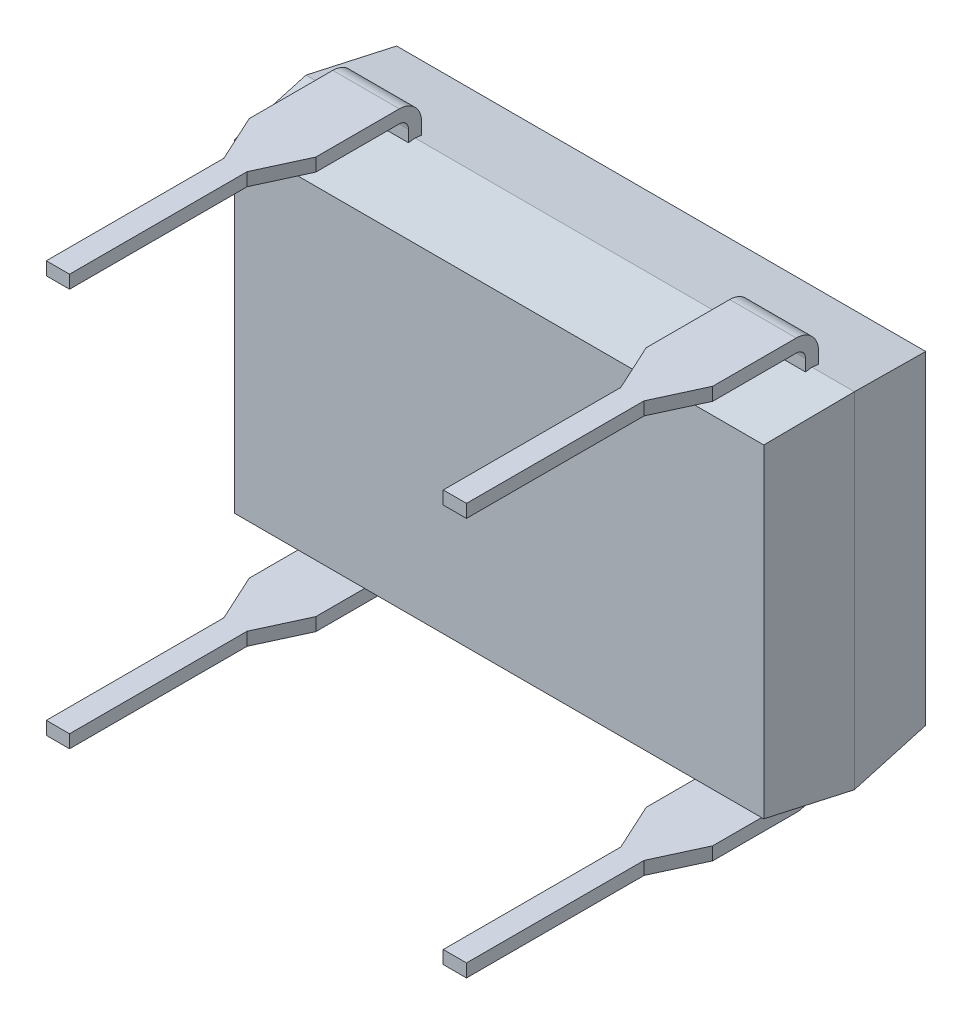
SolidWorks part; units mm, degrees
ref_plane "Plano frontal" through (0, 0, 0) normal (0, 0, 1) x (1, 0, 0)
ref_plane "Plano superior" through (0, 0, 0) normal (0, 1, 0) x (1, 0, 0)
ref_plane "Plano direito" through (0, 0, 0) normal (1, 0, 0) x (0, 0, -1)
sketch "Esboço1" plane through (0, 0, 0) normal (1, 0, 0) x (0, 0, -1)
  line L0 (0.9, 3.1) -> (0.9, -3.1)
  line L1 (0.9, -3.1) -> (2.45, -3.3)
  line L2 (2.45, -3.3) -> (4, -3.1)
  line L3 (4, -3.1) -> (4, 3.1)
  line L4 (4, 3.1) -> (2.45, 3.3)
  line L5 (2.45, 3.3) -> (0.9, 3.1)
  line L6 (2.45, 3.3) -> (2.45, -3.3) construction
  line L7 (4, 0) -> (2.45, 0) construction
  line L8 (2.45, 0) -> (0.9, 0) construction
  line L9 (0.9, 0) -> (0, 0) construction
  dimension "D1" = 6.6
  dimension "D2" = 6.2
  dimension "D3" = 3.1
  dimension "D4" = 0.9
extrude "Ressalto-extrusão1" add sketch "Esboço1" along normal mid plane 10.5
sketch "Esboço3" plane through (0, 0, 0) normal (0, 1, 0) x (1, 0, 0)
  line L0 (-5.25, 2.45) -> (-5.0199, 4.3768)
  line L1 (-5.0199, 4.3768) -> (-6.1863, 4.3768)
  line L2 (-6.1863, 4.3768) -> (-6.1863, 0.5232)
  line L3 (-6.1863, 0.5232) -> (-5.0199, 0.5232)
  line L4 (-5.0199, 0.5232) -> (-5.25, 2.45)
  line L5 (-6.1863, 2.45) -> (-5.25, 2.45) construction
  line L6 (-5.25, 0.9) -> (-5.25, 2.45) construction
  dimension "D1" = 6.81
  dimension "D2" = 3.8537
  dimension "D3" = 1.1665
extrude "Corte-extrusão2" cut sketch "Esboço3" against normal mid plane 7.1
mirror "Espelhar1" about plane through (0, 0, 0) normal (1, 0, 0) of "Corte-extrusão2"
sketch "Esboço8" plane through (0, 0, -4) normal (0, 0, -1) x (-1, 0, 0)
  line L0 (5.0649, -3.1) -> (5.0649, 3.1) construction
  circle A0 centre (5.0649, 0) radius 1
  dimension "D1" = 2
extrude "Corte-extrusão5" cut sketch "Esboço8" against normal up to vertex (1.55 mm away)
ref_plane "Plano1" through (0, 3.3, 0) normal (0, 1, 0) x (1, 0, 0)
sketch "Esboço6" plane through (0, 3.3, 0) normal (0, 1, 0) x (1, 0, 0)
  line L0 (-3.1625, 2.45) -> (0, 2.45) construction
  line L1 (-4.4375, 2.575) -> (-3.1625, 2.575)
  line L2 (-4.4375, 2.575) -> (-4.4375, 2.325)
  line L3 (-4.4375, 2.325) -> (-3.1625, 2.325)
  line L4 (-3.1625, 2.575) -> (-3.1625, 2.325)
  line L5 (5.25, 2.45) -> (-5.25, 2.45) construction
  line L6 (-3.8, 2.575) -> (-3.8, 2.325) construction
  line L7 (0, 5.2905) -> (0, -0.8303) construction
  point P14 (0, 0)
  dimension "D1" = 0.25
  dimension "D2" = 1.275
  dimension "D3" = 1.45
extrude "Ressalto-extrusão2" add sketch "Esboço6" along normal mid plane 0.05
sketch "Esboço7" plane through (0, 3.325, 0) normal (0, 1, 0) x (1, 0, 0)
  line L0 (-4.4375, 2.575) -> (-4.4375, 2.325) construction
  line L1 (-3.1625, 2.575) -> (-4.4375, 2.575) construction
  line L2 (-3.1625, 2.325) -> (-3.1625, 2.575) construction
  line L3 (-4.4375, 2.325) -> (-3.1625, 2.325) construction
  line L4 (-4.4375, 2.575) -> (-4.4375, 2.325)
  line L5 (-3.1625, 2.575) -> (-4.4375, 2.575)
  line L6 (-3.1625, 2.325) -> (-3.1625, 2.575)
  line L7 (-4.4375, 2.325) -> (-3.1625, 2.325)
  line L8 (-4.4375, 2.45) -> (-3.1625, 2.45) construction
sketch3d "3DSketch1"
  line L0 (-3.8, 3.325, -2.45) -> (-3.8, 3.51, -2.45)
  line L1 (-3.8, 3.325, -2.45) -> (-3.8, 0, -2.45) construction
  line L2 (-4.4375, 3.325, -2.45) -> (-3.1625, 3.325, -2.45) construction
  line L3 (-3.8, 3.81, -2.15) -> (-3.8, 3.81, 0.35)
  line L4 (-3.8, 0, -2.45) -> (0, 0, 0) construction
  line L5 (-5.0649, 2.7669, -0.9) -> (-4.7149, 5.6108, -0.9539) construction
  line L6 (-5.0649, 3.1, -0.9) -> (-5.0649, -3.1, -0.9) construction
  arc A0 (-3.8, 3.51, -2.45) -> (-3.8, 3.81, -2.15) centre (-3.8, 3.51, -2.15) ccw
  point P5 (-3.5, 3.51, -2.15)
  dimension "D3" = 0.3
  dimension "D1" = 2.8
  dimension "D2" = 3.81
sweep "Varredura1" add profiles "Esboço7" path "3DSketch1"
sketch "Esboço9" plane through (0, 3.935, 0) normal (0, 1, 0) x (1, 0, 0)
  line L0 (-4.0225, -0.35) -> (-4.4375, 0.55)
  line L1 (-3.1625, -0.35) -> (-4.4375, -0.35) construction
  line L3 (-4.4375, 2.15) -> (-4.4375, -0.35) construction
  line L4 (-4.4375, 0.55) -> (-4.4375, -0.55)
  line L5 (-4.4375, -0.55) -> (-3.1625, -0.55)
  line L6 (-3.1625, -0.55) -> (-3.1625, 0.55)
  line L7 (-3.1625, 2.15) -> (-3.1625, -0.35) construction
  line L8 (-3.1625, 0.55) -> (-3.5775, -0.35)
  line L9 (-3.5775, -0.35) -> (-4.0225, -0.35)
  line L10 (-3.8, -0.35) -> (-3.8, 2.15) construction
  line L11 (-3.1625, 2.15) -> (-4.4375, 2.15) construction
  dimension "D1" = 0.9
  dimension "D2" = 0.445
  dimension "D3" = 0.2
extrude "Corte-extrusão6" cut sketch "Esboço9" against normal up to next
sketch "Esboço10" plane through (0, 0, 0.35) normal (0, 0, 1) x (1, 0, 0)
  line L0 (-3.5775, 3.935) -> (-4.0225, 3.935) construction
  line L1 (-4.0225, 3.935) -> (-4.0225, 3.685) construction
  line L2 (-4.0225, 3.685) -> (-3.5775, 3.685) construction
  line L3 (-3.5775, 3.685) -> (-3.5775, 3.935) construction
  line L4 (-3.5775, 3.935) -> (-4.0225, 3.935)
  line L5 (-4.0225, 3.935) -> (-4.0225, 3.685)
  line L6 (-4.0225, 3.685) -> (-3.5775, 3.685)
  line L7 (-3.5775, 3.685) -> (-3.5775, 3.935)
extrude "Ressalto-extrusão3" add sketch "Esboço10" along normal blind 3.4
mirror "Espelhar2" about plane through (0, 0, 0) normal (0, 1, 0) of "Ressalto-extrusão3", "Corte-extrusão6", "Varredura1", "Ressalto-extrusão2"
mirror "Simetría1" about plane through (0, 0, 0) normal (1, 0, 0) of "Espelhar2", "Ressalto-extrusão2", "Varredura1", "Corte-extrusão6", "Ressalto-extrusão3"
